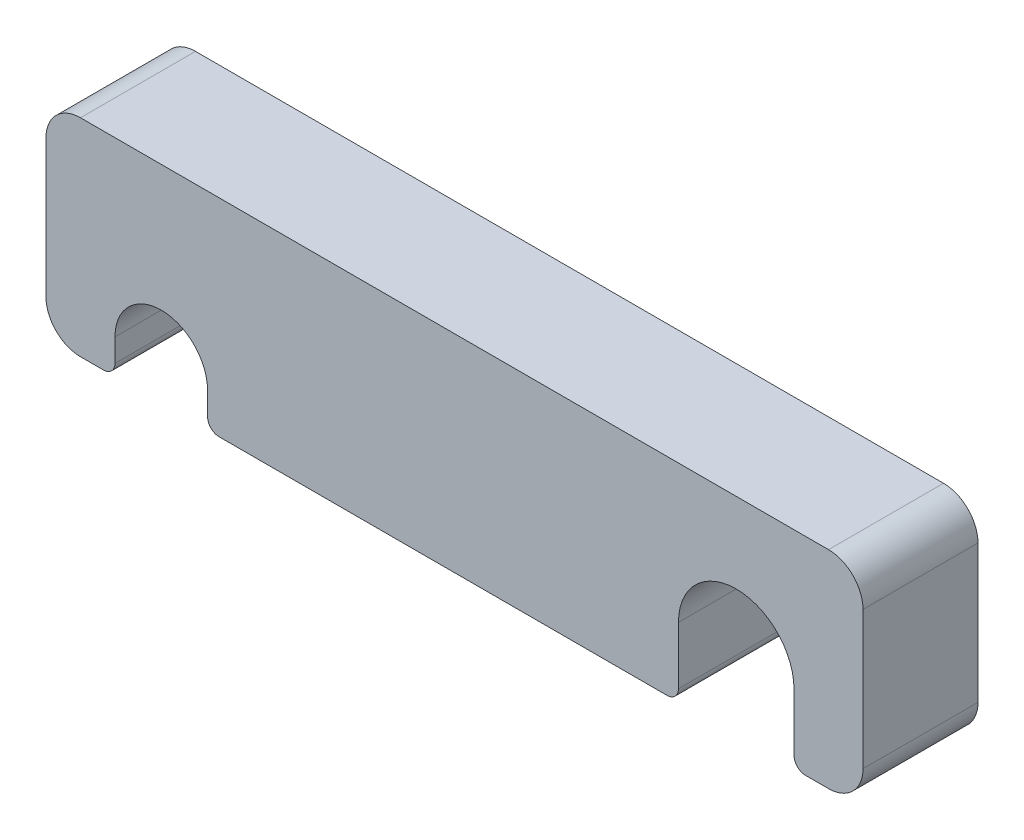
SolidWorks part; units mm, degrees
material "ABS"
ref_plane "Front Plane" through (0, 0, 0) normal (0, 0, 1) x (1, 0, 0)
ref_plane "Top Plane" through (0, 0, 0) normal (0, 1, 0) x (1, 0, 0)
ref_plane "Right Plane" through (0, 0, 0) normal (1, 0, 0) x (0, 0, -1)
sketch "Sketch1" plane through (0, 0, 0) normal (0, 0, 1) x (1, 0, 0)
  line L0 (6, 3) -> (6, 1)
  line L1 (5, 0) -> (3, 0)
  line L2 (0, 3) -> (0, 15)
  line L3 (3, 18) -> (68.05, 18)
  line L4 (71.05, 15) -> (71.05, 3)
  line L5 (68.05, 0) -> (66.05, 0)
  line L6 (65.05, 1) -> (65.05, 6)
  line L7 (55, 6) -> (55, 1)
  line L8 (54, 0) -> (15.05, 0)
  line L9 (14.05, 1) -> (14.05, 3)
  arc A0 (14.05, 3) -> (6, 3) centre (10.025, 3) ccw
  arc A1 (65.05, 6) -> (55, 6) centre (60.025, 6) ccw
  arc A2 (68.05, 0) -> (71.05, 3) centre (68.05, 3) ccw
  arc A3 (71.05, 15) -> (68.05, 18) centre (68.05, 15) ccw
  arc A4 (3, 0) -> (0, 3) centre (3, 3) cw
  arc A5 (0, 15) -> (3, 18) centre (3, 15) cw
  arc A6 (66.05, 0) -> (65.05, 1) centre (66.05, 1) cw
  arc A7 (54, 0) -> (55, 1) centre (54, 1) ccw
  arc A8 (15.05, 0) -> (14.05, 1) centre (15.05, 1) cw
  arc A9 (5, 0) -> (6, 1) centre (5, 1) ccw
  point P21 (0, 0)
  point P24 (0, 18)
  point P31 (14.05, 0)
  point P34 (6, 0)
  dimension "D1" = 8.05
  dimension "D2" = 10.05
  dimension "D4" = 3
  dimension "D5" = 3
  dimension "D8" = 50
  dimension "D9" = 3
  dimension "D10" = 1
  dimension "D3" = 6
  dimension "D6" = 18
  dimension "D7" = 6
extrude "Boss-Extrude1" add sketch "Sketch1" along normal blind 10
